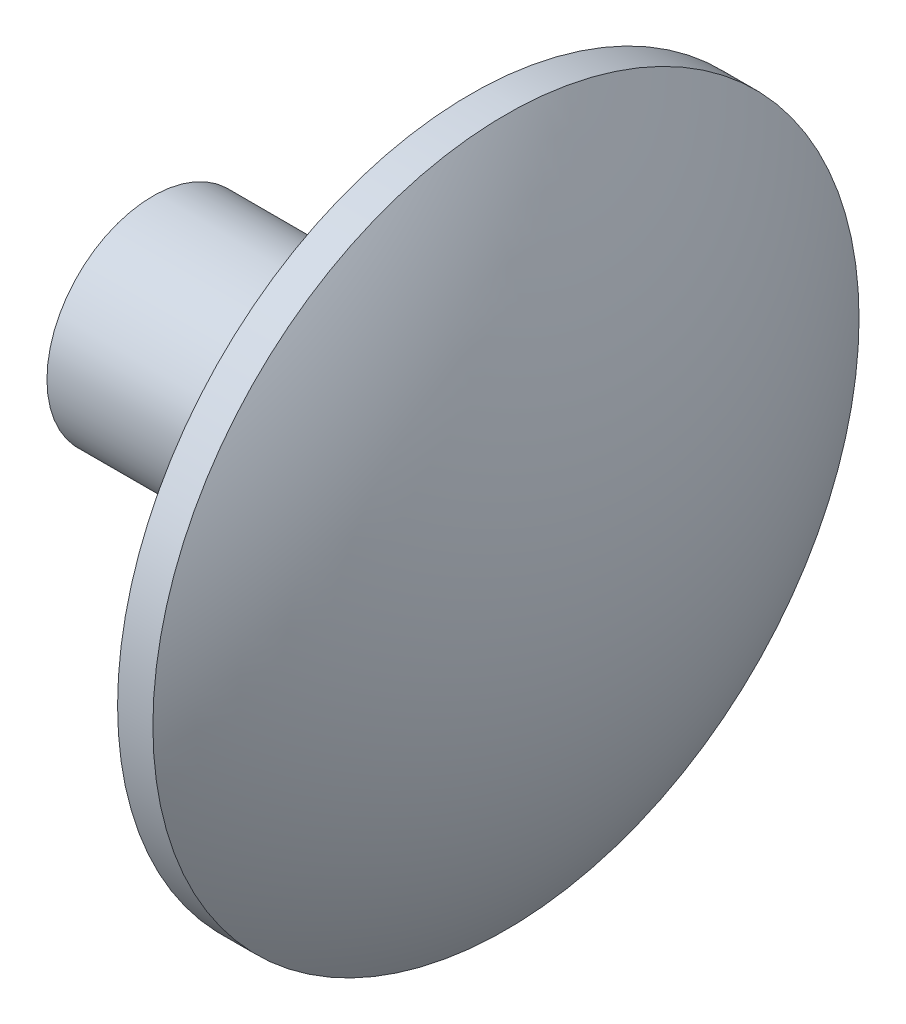
SolidWorks part; units mm, degrees
material "Copper"
ref_plane "Front Plane" through (0, 0, 0) normal (0, 0, 1) x (1, 0, 0)
ref_plane "Top Plane" through (0, 0, 0) normal (0, 1, 0) x (1, 0, 0)
ref_plane "Right Plane" through (0, 0, 0) normal (1, 0, 0) x (0, 0, -1)
sketch "Sketch1" plane through (0, 0, 0) normal (1, 0, 0) x (0, 0, -1)
  circle A0 centre (0, 0) radius 10
extrude "Boss-Extrude1" add sketch "Sketch1" along normal blind 1
sketch "Sketch2" plane through (0, 0, 0) normal (0, 1, 0) x (1, 0, 0)
  line L0 (1, 0) -> (4, 0)
  line L1 (1, -10) -> (1, 10) construction
  line L2 (1, 0) -> (1, 10)
  arc A0 (4, 0) -> (1, 10) centre (-14.1667, 0) ccw
revolve "Revolve1" add sketch "Sketch2" angle 360 about L0
sketch "Sketch3" plane through (0, 0, 0) normal (-1, 0, 0) x (0, 0, 1)
  line L1 (3, 3) -> (-3, 3)
  line L2 (3, 3) -> (3, -3)
  line L3 (3, -3) -> (-3, -3)
  line L4 (-3, 3) -> (-3, -3)
  line L5 (3, 3) -> (-3, -3) construction
  line L6 (3, -3) -> (-3, 3) construction
  point P0 (0, 0)
  dimension "6" = 6
extrude "Boss-Extrude2" add sketch "Sketch3" along normal blind 2
sketch "Sketch4" plane through (-2, 0, 0) normal (-1, 0, 0) x (0, 0, 1)
  circle A0 centre (0, 0) radius 3
extrude "Boss-Extrude3" add sketch "Sketch4" along normal blind 7
sketch "Sketch5" plane through (-9, 0, 0) normal (-1, 0, 0) x (0, 0, 1)
  circle A0 centre (0, 0) radius 2
hole_wizard "M5 Tapped Hole1" positions "Sketch12" profile "Sketch14" tap size "M5" standard "ISO"
sketch "Sketch12" plane through (-9, 0, 0) normal (-1, 0, 0) x (0, 0, 1)
  point P0 (0, 0)
cosmetic thread "Hole Thread1" parameters "D1"=7, "D2"=5
sketch "Sketch14" plane through (-9, 0, 0) normal (0, 1, 0) x (0, 0, 1)
  line L0 (0, 0) -> (0, 8.2618)
  line L1 (0, 8.2618) -> (2.1, 7)
  line L2 (2.1, 7) -> (2.1, 0)
  line L5 (2.1, 0) -> (0, 0)
  line L10 (0, 8.2618) -> (-2.1, 7) construction
  line L11 (0, -6.35) -> (0, 107.95) construction
  dimension "Tap Drill Dia." = 4.2
  dimension "Tap Drill Depth" = 7
  dimension "Drill Angle" = 118
